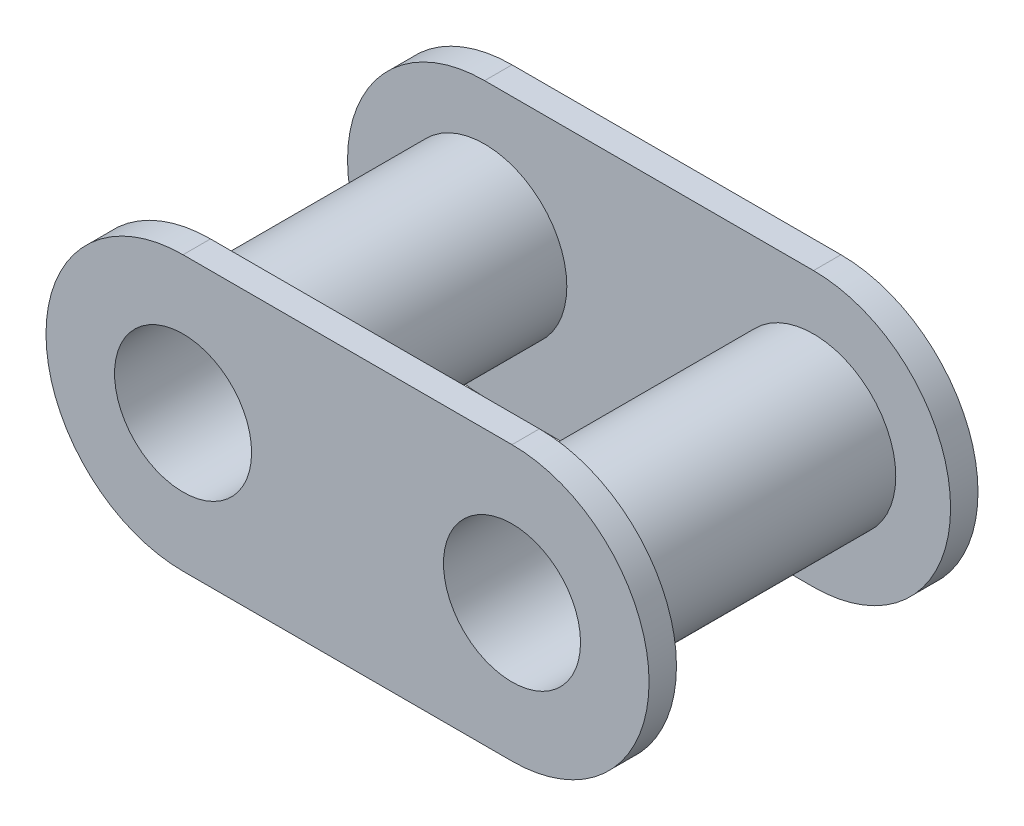
SolidWorks part; units mm, degrees
ref_plane "Front Plane" through (0, 0, 0) normal (0, 0, 1) x (1, 0, 0)
ref_plane "Top Plane" through (0, 0, 0) normal (0, 1, 0) x (1, 0, 0)
ref_plane "Right Plane" through (0, 0, 0) normal (1, 0, 0) x (0, 0, -1)
sketch "Sketch1" plane through (0, 0, 0) normal (0, 0, 1) x (1, 0, 0)
  line L0 (-3, 0) -> (3, 0) construction
  line L1 (-3, 2.5) -> (3, 2.5)
  line L2 (-3, -2.5) -> (3, -2.5)
  arc A0 (-3, 2.5) -> (-3, -2.5) centre (-3, 0) ccw
  arc A1 (3, -2.5) -> (3, 2.5) centre (3, 0) ccw
  circle A2 centre (-3, 0) radius 1.25
  circle A3 centre (3, 0) radius 1.25
  point P3 (0, 0)
  dimension "D2" = 2.5
  dimension "D3" = 2.5
  dimension "D1" = 6
extrude "Boss-Extrude1" add sketch "Sketch1" along normal blind 0.5
sketch "Sketch2" plane through (0, 0, 0.5) normal (0, 0, 1) x (1, 0, 0)
  circle A0 centre (-3, 0) radius 1.25 construction
  circle A1 centre (-3, 0) radius 1.25
  circle A2 centre (3, 0) radius 1.25 construction
  circle A3 centre (3, 0) radius 1.25
extrude "Extrude-Thin1" add sketch "Sketch2" along normal blind 2.5 thin
ref_plane "Plane1" through (0, 0, 3) normal (0, 0, 1) x (1, 0, 0)
mirror "Mirror1" about plane through (0, 0, 3) normal (0, 0, 1) of "Boss-Extrude1", "Extrude-Thin1"
